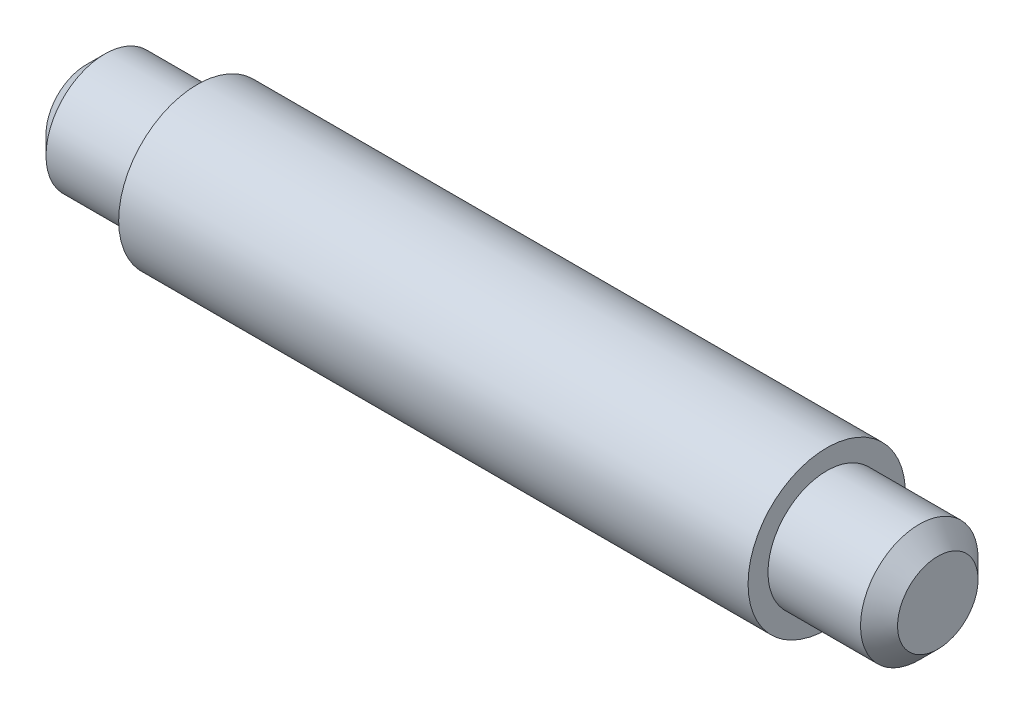
SolidWorks part; units mm, degrees
ref_plane "Front Plane" through (0, 0, 0) normal (0, 0, 1) x (1, 0, 0)
ref_plane "Top Plane" through (0, 0, 0) normal (0, 1, 0) x (1, 0, 0)
ref_plane "Right Plane" through (0, 0, 0) normal (1, 0, 0) x (0, 0, -1)
sketch "Sketch2" plane through (0, 0, 0) normal (0, 0, 1) x (1, 0, 0)
  line L0 (0, 0) -> (46, 0)
  line L1 (46, 0) -> (46, 2.175)
  line L2 (45, 3.175) -> (40, 3.175)
  line L3 (40, 3.175) -> (40, 4.25)
  line L4 (40, 4.25) -> (6, 4.25)
  line L5 (6, 4.25) -> (6, 3.175)
  line L6 (6, 3.175) -> (1, 3.175)
  line L7 (0, 2.175) -> (0, 0)
  line L8 (1, 3.175) -> (0, 2.175)
  line L9 (46, 2.175) -> (45, 3.175)
  point P4 (46, 3.175)
  point P9 (0, 3.175)
  dimension "D1" = 6
  dimension "D2" = 34
  dimension "D3" = 3.175
  dimension "D4" = 4.25
  dimension "D5" = 46
revolve "Revolve3" add sketch "Sketch2" angle 360 about L0
